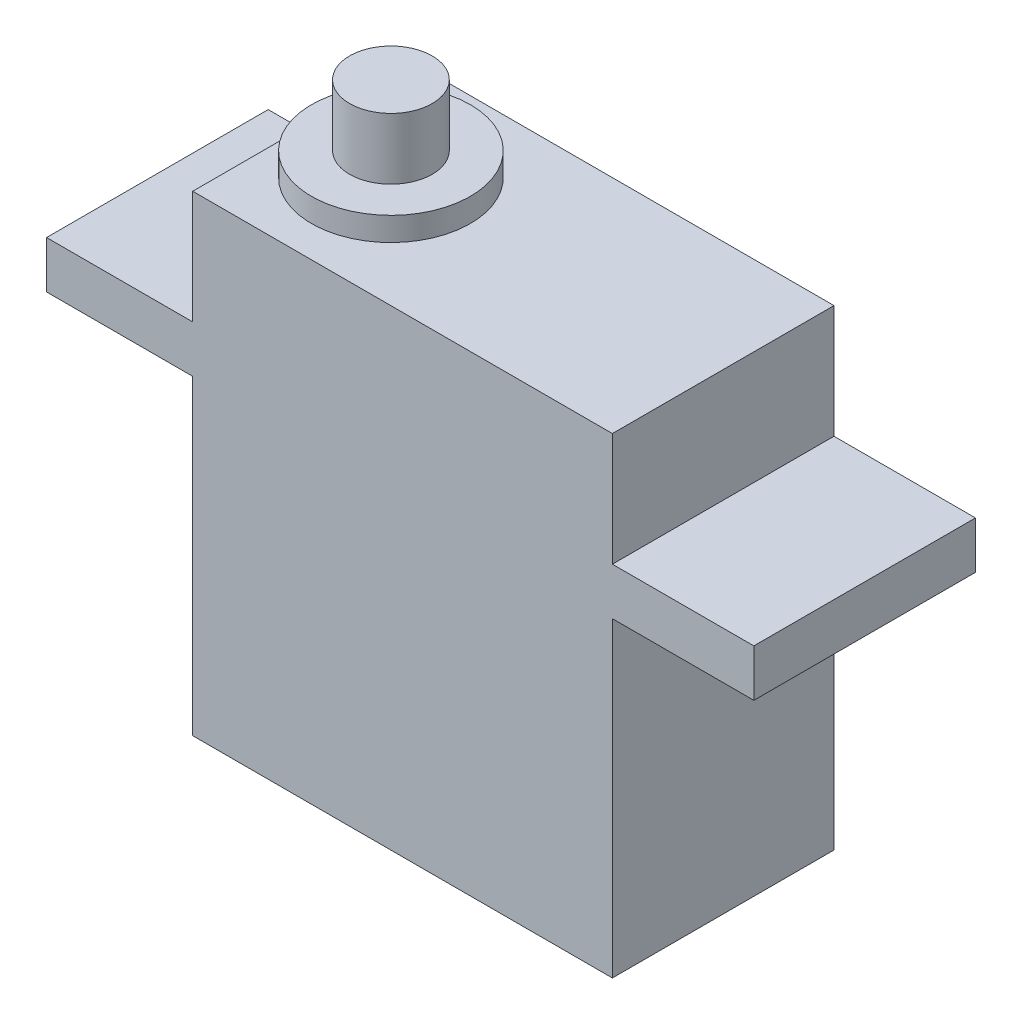
SolidWorks part; units mm, degrees
ref_plane "Front Plane" through (0, 0, 0) normal (0, 0, 1) x (1, 0, 0)
ref_plane "Top Plane" through (0, 0, 0) normal (0, 1, 0) x (1, 0, 0)
ref_plane "Right Plane" through (0, 0, 0) normal (1, 0, 0) x (0, 0, -1)
sketch "Sketch1" plane through (0, 0, 0) normal (0, 1, 0) x (1, 0, 0)
  line L1 (0, 0) -> (22.606, 0)
  line L2 (0, 0) -> (0, 11.938)
  line L3 (0, 11.938) -> (22.606, 11.938)
  line L4 (22.606, 0) -> (22.606, 11.938)
  dimension "D1" = 11.938
  dimension "D2" = 22.606
extrude "Boss-Extrude1" add sketch "Sketch1" along normal blind 25.4
sketch "Sketch2" plane through (0, 25.4, 0) normal (0, 1, 0) x (1, 0, 0)
  circle A0 centre (4.707, 5.969) radius 2.2247
extrude "Boss-Extrude2" add sketch "Sketch2" along normal blind 4.572
sketch "Sketch3" plane through (0, 25.4, 0) normal (0, 1, 0) x (1, 0, 0)
  circle A0 centre (4.707, 5.969) radius 4.2797
extrude "Boss-Extrude3" add sketch "Sketch3" along normal blind 1.27
sketch "Sketch4" plane through (22.606, 0, 0) normal (1, 0, 0) x (0, 0, -1)
  line L0 (0, 25.4) -> (0, 0) construction
  line L1 (0, 19.304) -> (11.938, 19.304)
  line L2 (0, 19.304) -> (0, 16.764)
  line L3 (0, 16.764) -> (11.938, 16.764)
  line L4 (11.938, 19.304) -> (11.938, 16.764)
  line L5 (11.938, 25.4) -> (11.938, 0) construction
  line L6 (0, 0) -> (11.938, 0) construction
  dimension "D1" = 16.764
  dimension "D2" = 19.304
extrude "Boss-Extrude4" add sketch "Sketch4" along normal blind 7.62 and the other way blind 30.48
